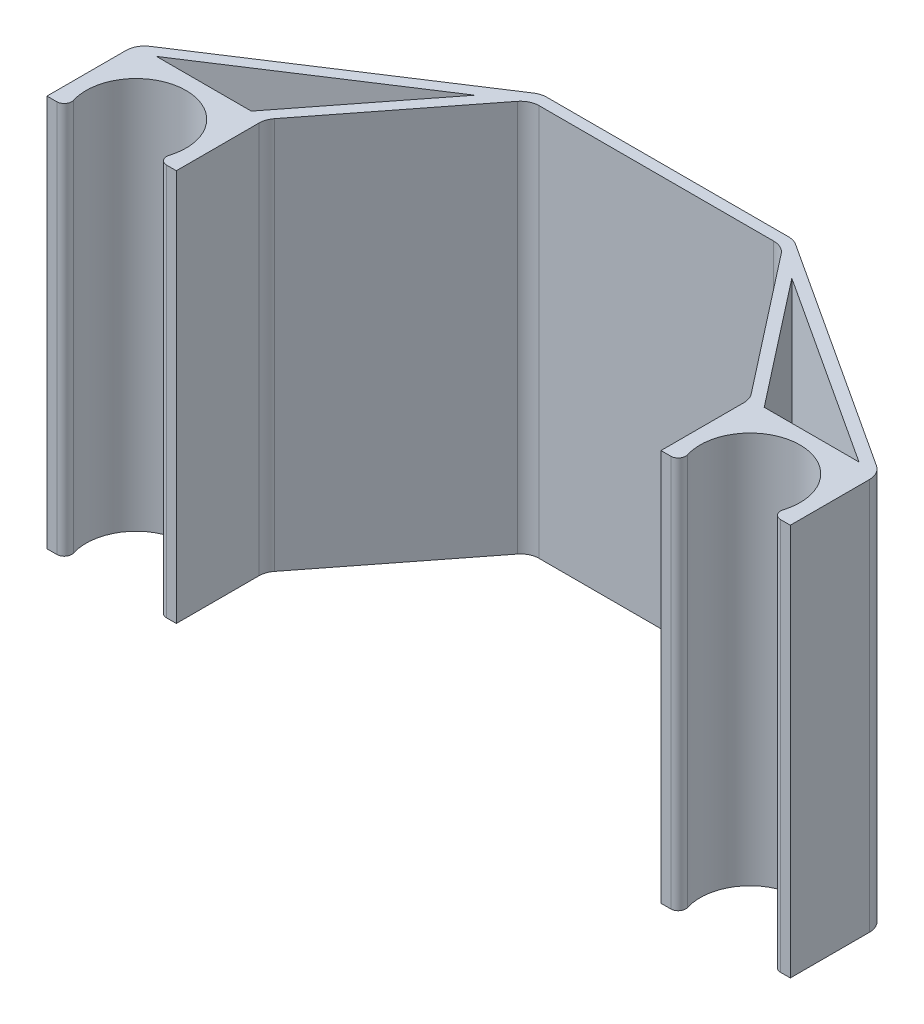
SolidWorks part; units mm, degrees
ref_plane "Front Plane" through (0, 0, 0) normal (0, 0, 1) x (1, 0, 0)
ref_plane "Top Plane" through (0, 0, 0) normal (0, 1, 0) x (1, 0, 0)
ref_plane "Right Plane" through (0, 0, 0) normal (1, 0, 0) x (0, 0, -1)
sketch "Sketch1" plane through (0, 0, 0) normal (0, 1, 0) x (1, 0, 0)
  line L0 (0, 0) -> (-34, 0)
  line L1 (-34, 0) -> (-100, -43)
  line L2 (-100, -43) -> (-100, -66.97)
  line L3 (-100, -66.97) -> (-97.3586, -66.97)
  line L4 (-67.8414, -66.97) -> (-65.2, -66.97)
  line L5 (-65.2, -66.97) -> (-65.2, -43)
  line L6 (-69.0047, -43) -> (-94.5043, -43)
  line L7 (-94.5043, -43) -> (-42.6567, -9.2205)
  line L8 (-34, -3) -> (0, -3)
  line L9 (0, -3) -> (0, 0)
  line L10 (-69.0047, -43) -> (-42.6567, -9.2205)
  line L11 (-34, -3) -> (-65.2, -43)
  arc A0 (-95.4481, -64.3784) -> (-69.7519, -64.3784) centre (-82.6, -60.4) cw
  arc A1 (-67.8414, -66.97) -> (-69.7519, -64.3784) centre (-67.8414, -64.97) cw
  arc A2 (-95.4481, -64.3784) -> (-97.3586, -66.97) centre (-97.3586, -64.97) cw
  dimension "D3" = 13.45
  dimension "D11" = 2
  dimension "D1" = 100
  dimension "D2" = 34.8
  dimension "D4" = 17.4
  dimension "D5" = 23.97
  dimension "D6" = 3
  dimension "D7" = 43
  dimension "D8" = 3
  dimension "D9" = 3
  dimension "D10" = 3
  dimension "D12" = 66
extrude "Boss-Extrude1" add sketch "Sketch1" along normal blind 105.5 contours L5 L11 L8 L9 L0 L1 L2 L3 A2 A0 A1 L4
mirror "Mirror1" about plane through (0, 105.5, 3) normal (-1, 0, 0) of "Boss-Extrude1"
fillet "Fillet1" radius 5 8 edges at (-100, 52.75, 43) (-34, 52.75, 0) (34, 52.75, 0) (100, 52.75, 43) (65.2, 52.75, 43) (34, 52.75, 3) (-34, 52.75, 3) (-65.2, 52.75, 43)
